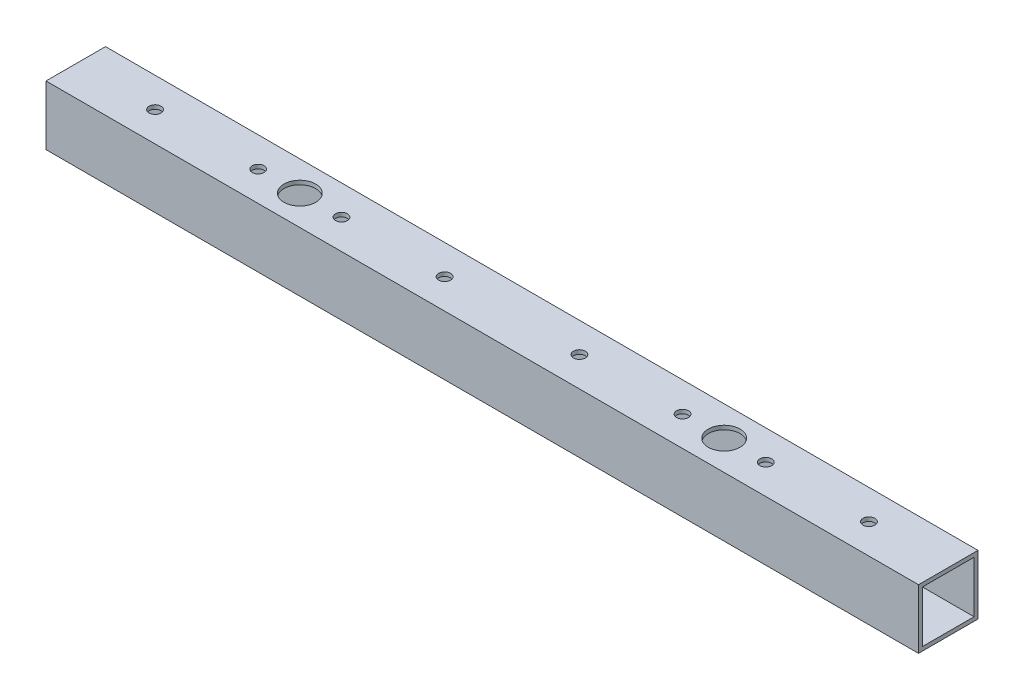
SolidWorks part; units mm, degrees
ref_plane "前视基准面" through (0, 0, 0) normal (0, 0, 1) x (1, 0, 0)
ref_plane "上视基准面" through (0, 0, 0) normal (0, 1, 0) x (1, 0, 0)
ref_plane "右视基准面" through (0, 0, 0) normal (1, 0, 0) x (0, 0, -1)
sketch "草图1" plane through (0, 0, 0) normal (1, 0, 0) x (0, 0, -1)
  line L0 (-6.5, 6.5) -> (6.5, 6.5)
  line L1 (-7.5, -7.5) -> (7.5, -7.5)
  line L2 (-7.5, -7.5) -> (-7.5, 7.5)
  line L3 (-7.5, 7.5) -> (7.5, 7.5)
  line L4 (7.5, -7.5) -> (7.5, 7.5)
  line L5 (-7.5, -7.5) -> (7.5, 7.5) construction
  line L6 (-7.5, 7.5) -> (7.5, -7.5) construction
  line L7 (6.5, -6.5) -> (6.5, 6.5)
  line L8 (-6.5, -6.5) -> (6.5, -6.5)
  line L9 (-6.5, -6.5) -> (-6.5, 6.5)
  point P0 (0, 0)
  dimension "D1" = 15
  dimension "D2" = 15
  dimension "D3" = 1
extrude "凸台-拉伸1" add sketch "草图1" along normal blind 220
sketch "草图2" plane through (0, 7.5, 0) normal (0, 1, 0) x (1, 0, 0)
  line L0 (0, 7.5) -> (0, -7.5) construction
  line L1 (110, -38.3342) -> (110, 23.3342) construction
  line L4 (220, -7.5) -> (0, -7.5) construction
  circle A0 centre (20, 0) radius 1.5
  circle A1 centre (46, 0) radius 1.5
  circle A2 centre (56.5, 0) radius 1.5
  circle A3 centre (67, 0) radius 1.5
  circle A4 centre (93, 0) radius 1.5
  circle A5 centre (127, 0) radius 1.5
  circle A6 centre (153, 0) radius 1.5
  circle A7 centre (163.5, 0) radius 1.5
  circle A8 centre (174, 0) radius 1.5
  circle A9 centre (200, 0) radius 1.5
  point P24 (110, -7.5)
  point P27 (110, -7.5)
  dimension "D1" = 20
  dimension "D2" = 46
  dimension "D3" = 56.5
  dimension "D4" = 67
  dimension "D5" = 93
  dimension "D6" = 0
extrude "切除-拉伸1" cut sketch "草图2" against normal blind 230
sketch "草图3" plane through (0, 7.5, 0) normal (0, 1, 0) x (1, 0, 0)
  circle A0 centre (56.5, 0) radius 4
  circle A1 centre (163.5, 0) radius 4
extrude "切除-拉伸2" cut sketch "草图3" against normal blind 3
sketch "草图4" plane through (0, -7.5, 0) normal (0, -1, 0) x (1, 0, 0)
  circle A0 centre (20, 0) radius 4
  circle A1 centre (46, 0) radius 4
  circle A2 centre (67, 0) radius 4
  circle A3 centre (93, 0) radius 4
  circle A4 centre (127, 0) radius 4
  circle A5 centre (153, 0) radius 4
  circle A6 centre (174, 0) radius 4
  circle A7 centre (200, 0) radius 4
extrude "切除-拉伸3" cut sketch "草图4" against normal blind 3
